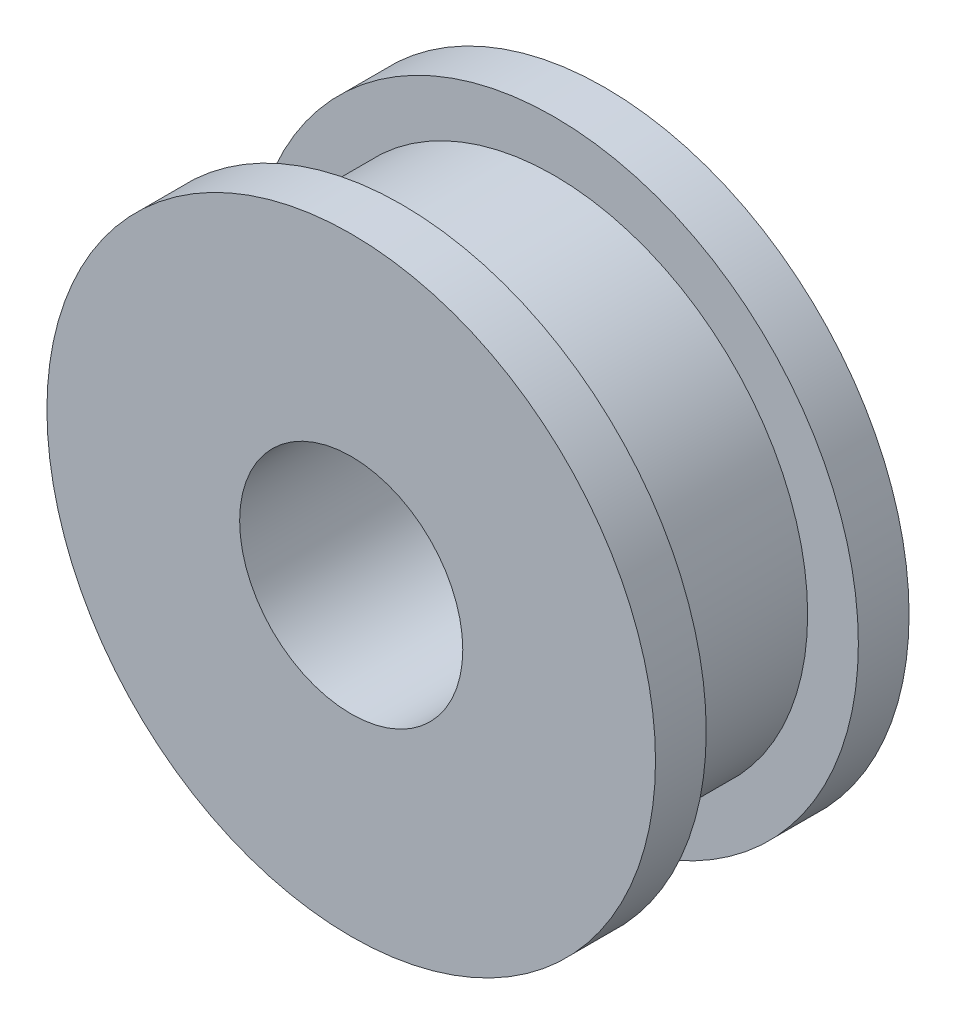
SolidWorks part; units mm, degrees
ref_plane "Ön Düzlem" through (0, 0, 0) normal (0, 0, 1) x (1, 0, 0)
ref_plane "Üst Düzlem" through (0, 0, 0) normal (0, 1, 0) x (1, 0, 0)
ref_plane "Sağ Düzlem" through (0, 0, 0) normal (1, 0, 0) x (0, 0, -1)
sketch "Çizim1" plane through (0, 0, 0) normal (0, 0, 1) x (1, 0, 0)
  circle A0 centre (0, 0) radius 25
  dimension "D1" = 50
extrude "Yükseklik-Ekstrüzyon1" add sketch "Çizim1" along normal blind 15
sketch "Çizim3" plane through (0, 0, 0) normal (0, 0, -1) x (-1, 0, 0)
  circle A0 centre (0, 0) radius 30
  dimension "D1" = 60
extrude "Yükseklik-Ekstrüzyon2" add sketch "Çizim3" along normal blind 5
sketch "Çizim4" plane through (0, 0, 15) normal (0, 0, 1) x (1, 0, 0)
  circle A0 centre (0, 0) radius 30
extrude "Yükseklik-Ekstrüzyon3" add sketch "Çizim4" along normal blind 5
sketch "Çizim5" plane through (0, 0, 20) normal (0, 0, 1) x (1, 0, 0)
  circle A0 centre (0, 0) radius 11
  dimension "D1" = 22
extrude "Kes-Ekstrüzyon1" cut sketch "Çizim5" against normal through all
